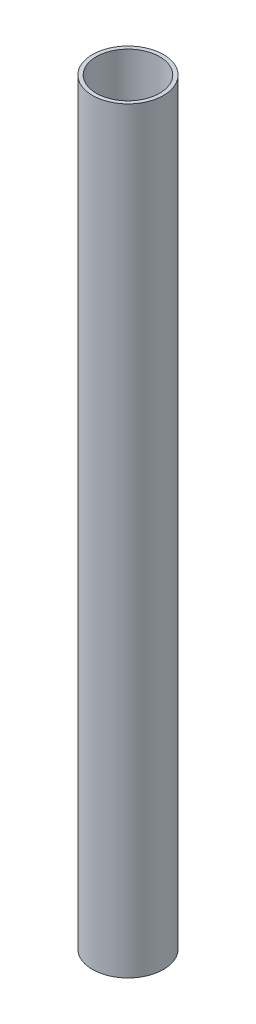
SolidWorks part; units mm, degrees
material "PP Homopolymer"
ref_plane "Front Plane" through (0, 0, 0) normal (0, 0, 1) x (1, 0, 0)
ref_plane "Top Plane" through (0, 0, 0) normal (0, 1, 0) x (1, 0, 0)
ref_plane "Right Plane" through (0, 0, 0) normal (1, 0, 0) x (0, 0, -1)
sketch "Sketch1" plane through (0, 0, 0) normal (0, 1, 0) x (1, 0, 0)
  circle A0 centre (0, 0) radius 33.5
  circle A1 centre (0, 0) radius 37.5
  dimension "D1" = 4
  dimension "D2" = 75
extrude "Boss-Extrude1" add sketch "Sketch1" along normal blind 800
sketch "Sketch2" plane through (0, 0, 0) normal (1, 0, 0) x (0, 0, -1)
  line L0 (-33.5, 650) -> (-30.5, 660)
  line L1 (-30.5, 660) -> (-33.5, 660)
  line L2 (-33.5, 660) -> (-33.5, 650)
  line L5 (0, 41.25) -> (0, -41.25) construction
  line L6 (41.25, 0) -> (-41.25, 0) construction
  point P7 (-32, 660)
  dimension "D1" = 33.5
  dimension "D2" = 3
  dimension "D3" = 660
  dimension "D4" = 10
revolve "Revolve1" add sketch "Sketch2" angle 360 about axis through (0, 800, 0) along (0, -1, 0)
equation "\"D1@Boss-Extrude1\"= 1100 - \"EB\""
equation "\"EB\" = 127"
